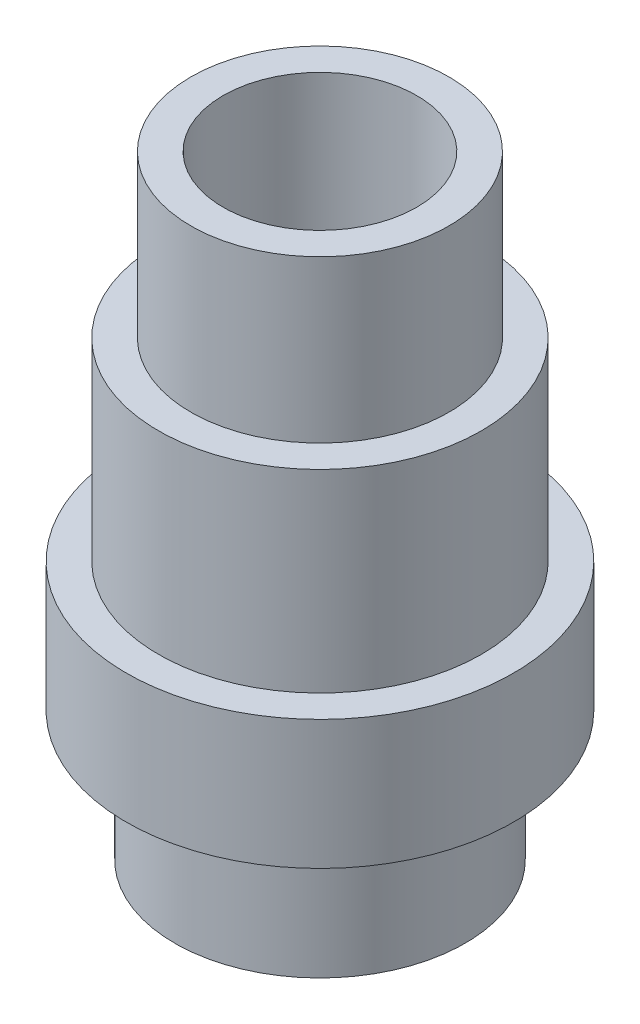
SolidWorks part; units mm, degrees
ref_plane "Front Plane" through (0, 0, 0) normal (0, 0, 1) x (1, 0, 0)
ref_plane "Top Plane" through (0, 0, 0) normal (0, 1, 0) x (1, 0, 0)
ref_plane "Right Plane" through (0, 0, 0) normal (1, 0, 0) x (0, 0, -1)
sketch "Sketch2" plane through (0, 0, 0) normal (0, 0, 1) x (1, 0, 0)
  line L0 (0, 108.9965) -> (0, -108.9965) construction
  line L1 (-15, -50.7135) -> (-15, 44.2865)
  line L2 (-15, 44.2865) -> (-20, 44.2865)
  line L3 (-20, 44.2865) -> (-20, 19.2865)
  line L4 (-20, 19.2865) -> (-25, 19.2865)
  line L5 (-25, 19.2865) -> (-25, -10.7135)
  line L6 (-25, -10.7135) -> (-30, -10.7135)
  line L7 (-30, -10.7135) -> (-30, -30.7135)
  line L8 (-30, -30.7135) -> (-22.5, -30.7135)
  line L9 (-22.5, -30.7135) -> (-22.5, -50.7135)
  line L10 (-22.5, -50.7135) -> (-15, -50.7135)
  point P2 (-38.3527, -28.7877)
  point P6 (0, 0)
  point P7 (0, 0)
  point P16 (0, 0)
  dimension "D1" = 95
  dimension "D2" = 25
  dimension "D3" = 30
  dimension "D4" = 55
  dimension "D5" = 40
  dimension "D6" = 50
  dimension "D7" = 20
  dimension "D8" = 5
  dimension "D9" = 45
  dimension "D10" = 60
revolve "Revolve1" add sketch "Sketch2" angle 360 about L0
